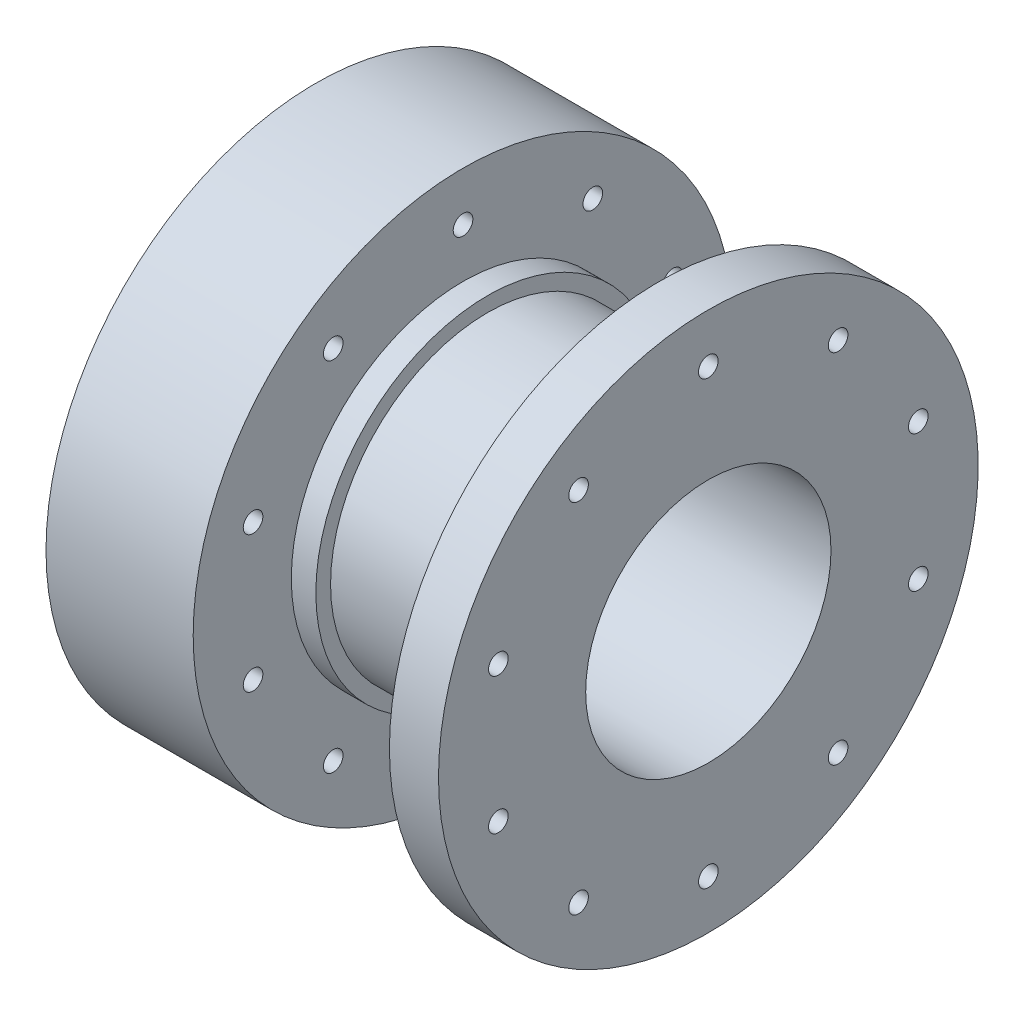
SolidWorks part; units mm, degrees
ref_plane "Front Plane" through (0, 0, 0) normal (0, 0, 1) x (1, 0, 0)
ref_plane "Top Plane" through (0, 0, 0) normal (0, 1, 0) x (1, 0, 0)
ref_plane "Right Plane" through (0, 0, 0) normal (1, 0, 0) x (0, 0, -1)
sketch "Sketch1" plane through (0, 0, 0) normal (0, 0, 1) x (1, 0, 0)
  line L0 (-97.5523, 0) -> (103.2428, 0) construction
  line L1 (-30, 25) -> (-30, 35)
  line L2 (0, 25) -> (-30, 25)
  line L3 (0, 25) -> (30, 25)
  line L4 (-30, 35) -> (-50, 35)
  line L5 (-50, 35) -> (-50, 40)
  line L6 (-50, 40) -> (-30, 40)
  line L7 (-30, 40) -> (-30, 50)
  line L8 (-30, 50) -> (-50, 50)
  line L9 (-50, 50) -> (-50, 55)
  line L10 (-50, 55) -> (-20, 55)
  line L11 (-20, 55) -> (-20, 35)
  line L12 (-20, 35) -> (-15, 35)
  line L13 (-15, 35) -> (-15, 32)
  line L14 (-15, 32) -> (15, 32)
  line L15 (15, 32) -> (15, 35)
  line L16 (15, 35) -> (20, 35)
  line L17 (20, 35) -> (20, 55)
  line L18 (20, 55) -> (30, 55)
  line L19 (30, 55) -> (30, 25)
revolve "Revolve1" add sketch "Sketch1" angle 360 about L0
sketch "Sketch2" plane through (30, 0, 0) normal (1, 0, 0) x (0, 0, -1)
  circle A0 centre (26.4503, 36.4058) radius 2
  circle A1 centre (42.7975, 13.9058) radius 2
  circle A2 centre (0, 45) radius 2
  circle A3 centre (42.7975, -13.9058) radius 2
  circle A4 centre (26.4503, -36.4058) radius 2
  circle A5 centre (0, -45) radius 2
  circle A6 centre (-26.4503, -36.4058) radius 2
  circle A7 centre (-42.7975, -13.9058) radius 2
  circle A8 centre (-42.7975, 13.9058) radius 2
  circle A9 centre (-26.4503, 36.4058) radius 2
  point P24 (0, 0)
  dimension "D1" = 45
  dimension "D2" = 10
extrude "Cut-Extrude1" cut sketch "Sketch2" against normal through all
